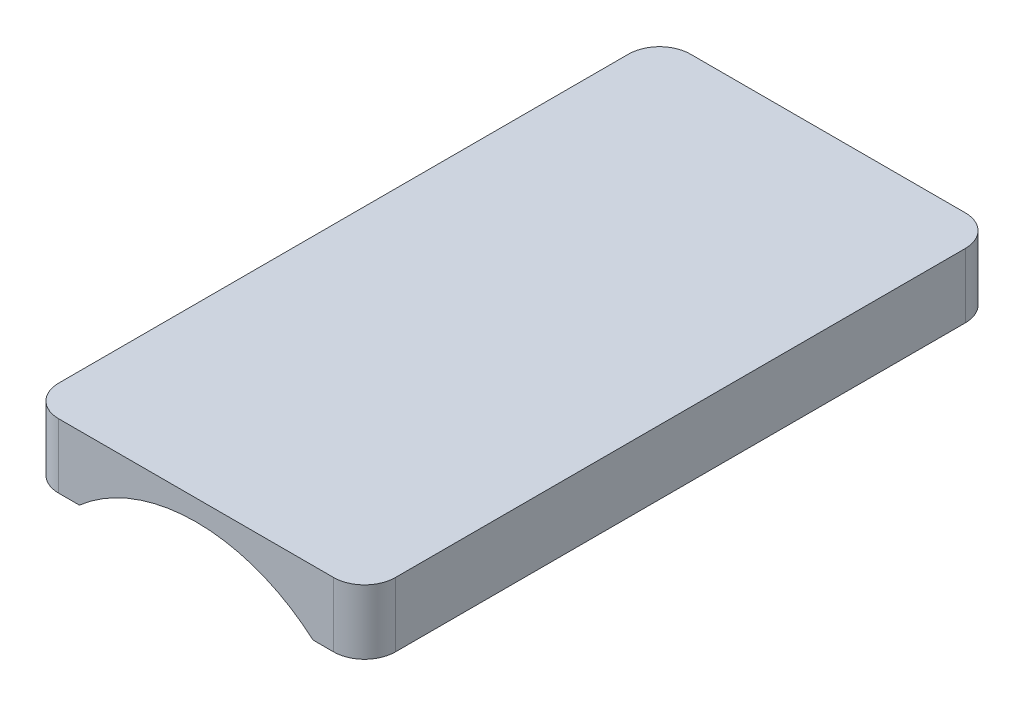
SolidWorks part; units mm, degrees
ref_plane "Front Plane" through (0, 0, 0) normal (0, 0, 1) x (1, 0, 0)
ref_plane "Top Plane" through (0, 0, 0) normal (0, 1, 0) x (1, 0, 0)
ref_plane "Right Plane" through (0, 0, 0) normal (1, 0, 0) x (0, 0, -1)
sketch "Sketch1" plane through (0, 0, 0) normal (1, 0, 0) x (0, 0, -1)
  line L0 (0, 0) -> (0, 6.25)
  line L1 (0, 6.25) -> (61.25, 6.25)
  line L2 (61.25, 6.25) -> (61.25, 0)
  line L3 (61.25, 0) -> (0, 0)
  dimension "D1" = 61.25
  dimension "D2" = 6.25
extrude "Boss-Extrude1" add sketch "Sketch1" along normal blind 32.65
sketch "Sketch2" plane through (0, 0, 0) normal (0, 0, 1) x (1, 0, 0)
  line L0 (32.65, 0) -> (0, 0) construction
  line L1 (5, 0) -> (27.65, 0)
  arc A0 (5, 0) -> (27.65, 0) centre (16.325, -12.9639) cw
  point P3 (16.325, 4.25)
  dimension "D1" = 4.25
  dimension "D2" = 5
  dimension "D3" = 5
extrude "Cut-Extrude1" cut sketch "Sketch2" against normal blind 35 and the other way through all
sketch "Sketch3" plane through (0, 0, -61.25) normal (0, 0, -1) x (-1, 0, 0)
  line L7 (-32.65, 6.25) -> (0, 6.25) construction
  line L12 (-11.175, 1) -> (-11.175, 5.25)
  line L13 (-11.175, 5.25) -> (-21.475, 5.25)
  line L15 (-21.475, 1) -> (-11.175, 1)
  line L16 (-21.475, 1) -> (-19.35, 3.125)
  line L17 (-19.35, 3.125) -> (-21.475, 5.25)
  line L18 (-32.65, 0) -> (0, 0) construction
  point P8 (-16.325, 5.25)
  point P9 (-11.175, 3.125)
  point P12 (-16.325, 6.25)
  dimension "D1" = 10.3
  dimension "D2" = 1
  dimension "D3" = 1
extrude "Cut-Extrude2" cut sketch "Sketch3" against normal blind 10
fillet "Fillet1" radius 3 4 edges at (0, 3.125, 0) (32.65, 3.125, 0) (32.65, 3.125, -61.25) (0, 3.125, -61.25)
